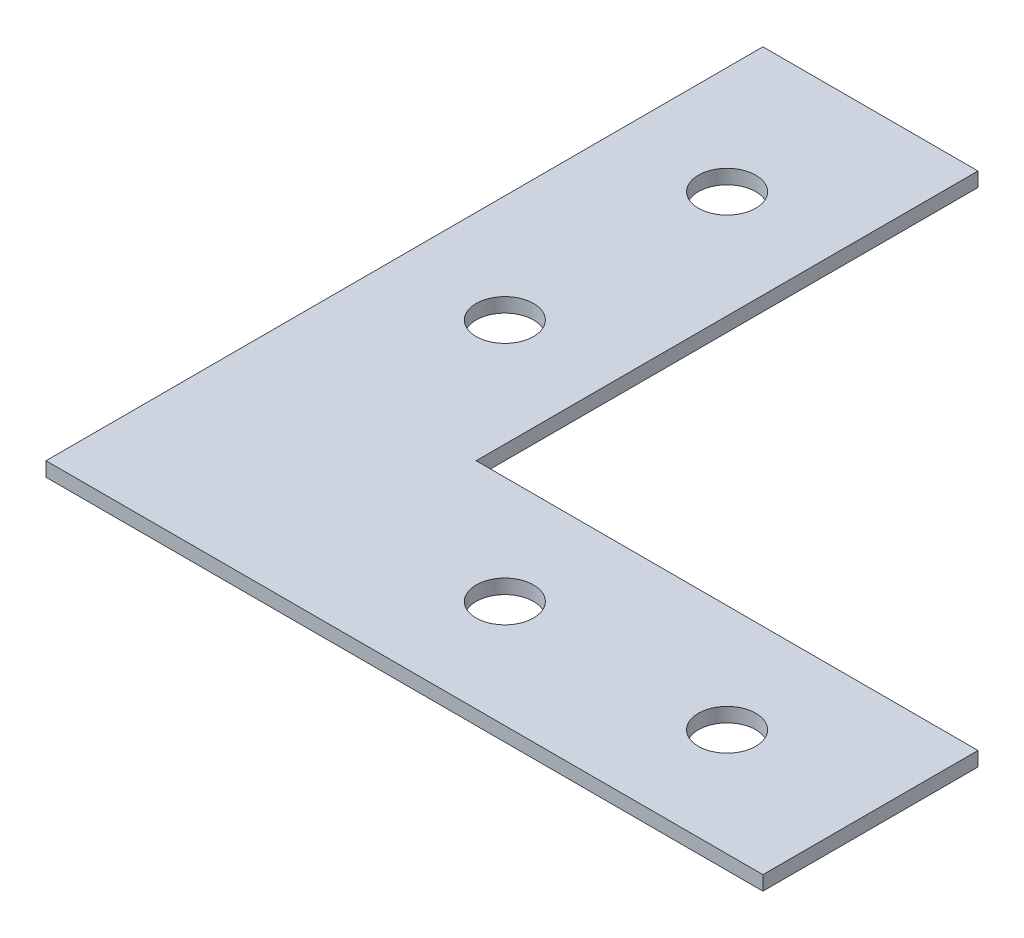
SolidWorks part; units mm, degrees
ref_plane "Front Plane" through (0, 0, 0) normal (0, 0, 1) x (1, 0, 0)
ref_plane "Top Plane" through (0, 0, 0) normal (0, 1, 0) x (1, 0, 0)
ref_plane "Right Plane" through (0, 0, 0) normal (1, 0, 0) x (0, 0, -1)
sketch "Sketch2" plane through (0, 0, 0) normal (0, 1, 0) x (1, 0, 0)
  line L0 (0, 0) -> (0, 50)
  line L1 (0, 50) -> (15, 50)
  line L2 (15, 50) -> (15, 15)
  line L3 (15, 15) -> (50, 15)
  line L4 (50, 15) -> (50, 0)
  line L5 (50, 0) -> (0, 0)
  dimension "D1" = 15
  dimension "D2" = 50
extrude "Boss-Extrude1" add sketch "Sketch2" along normal blind 1
sketch "Sketch4" plane through (0, 1, 0) normal (0, 1, 0) x (1, 0, 0)
  line L0 (0, 0) -> (50, 0) construction
  line L1 (15, 15) -> (0, 0)
  circle A0 centre (7.5, 24.5) radius 2
  circle A1 centre (7.5, 40) radius 2
  circle A2 centre (24.5, 7.5) radius 2
  circle A3 centre (40, 7.5) radius 2
  dimension "D2" = 4
  dimension "D3" = 7.5
  dimension "D4" = 24.5
  dimension "D5" = 15.5
extrude "Cut-Extrude1" cut sketch "Sketch4" against normal through all contours A1 | A0 | A2 | A3
